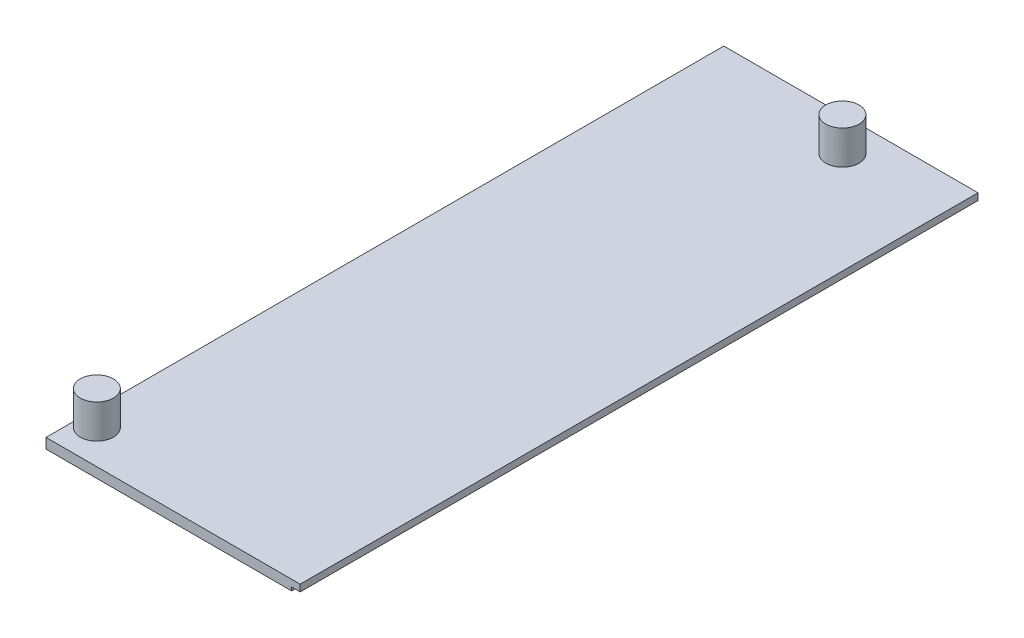
SolidWorks part; units mm, degrees
ref_plane "Front Plane" through (0, 0, 0) normal (0, 0, 1) x (1, 0, 0)
ref_plane "Top Plane" through (0, 0, 0) normal (0, 1, 0) x (1, 0, 0)
ref_plane "Right Plane" through (0, 0, 0) normal (1, 0, 0) x (0, 0, -1)
sketch "Sketch1" plane through (0, 0, 0) normal (0, 0, 1) x (1, 0, 0)
  line L1 (0, 0) -> (75, 0)
  line L2 (0, 0) -> (0, 3)
  line L3 (0, 3) -> (75, 3)
  line L4 (75, 0) -> (75, 3)
  dimension "D1" = 3
  dimension "D2" = 75
extrude "Boss-Extrude1" add sketch "Sketch1" along normal blind 200
sketch "Sketch2" plane through (0, 3, 0) normal (0, 1, 0) x (1, 0, 0)
  line L0 (75, -200) -> (75, 0) construction
  line L1 (112.5, 0) -> (-112.5, 0)
  line L2 (112.5, 0) -> (112.5, -200)
  line L3 (112.5, -200) -> (-112.5, -200)
  line L4 (-112.5, 0) -> (-112.5, -200)
  line L5 (100, -200) -> (-100, -200)
  line L6 (100, -200) -> (100, 0)
  line L7 (100, 0) -> (-100, 0)
  line L8 (-100, -200) -> (-100, 0)
  line L9 (75, -200) -> (0, -200) construction
  line L10 (75, 0) -> (0, 0) construction
  circle A0 centre (5, -190) radius 4.9
  circle A1 centre (45, -10) radius 4.9
  point P15 (8.9916, -185.9159)
  dimension "D4" = 10
  dimension "D5" = 40
  dimension "D6" = 9.8
  dimension "D7" = 9.8
  dimension "D8" = 10
  dimension "D9" = 55
  dimension "D1" = 225
  dimension "D2" = 12.5
  dimension "D3" = 12.5
  dimension "D10" = 25
extrude "Boss-Extrude2" add sketch "Sketch2" along normal blind 10 contours A1 | A0
sketch "Sketch3" plane through (0, 0, 0) normal (0, -1, 0) x (1, 0, 0)
  line L0 (0, 0) -> (75, 0) construction
  line L5 (75, 200) -> (72.5, 200)
  line L20 (75, 200) -> (75, 0)
  line L21 (75, 0) -> (72.5, 0)
  line L22 (72.5, 200) -> (72.5, 0)
  dimension "D1" = 2.5
extrude "Cut-Extrude1" cut sketch "Sketch3" against normal blind 1
